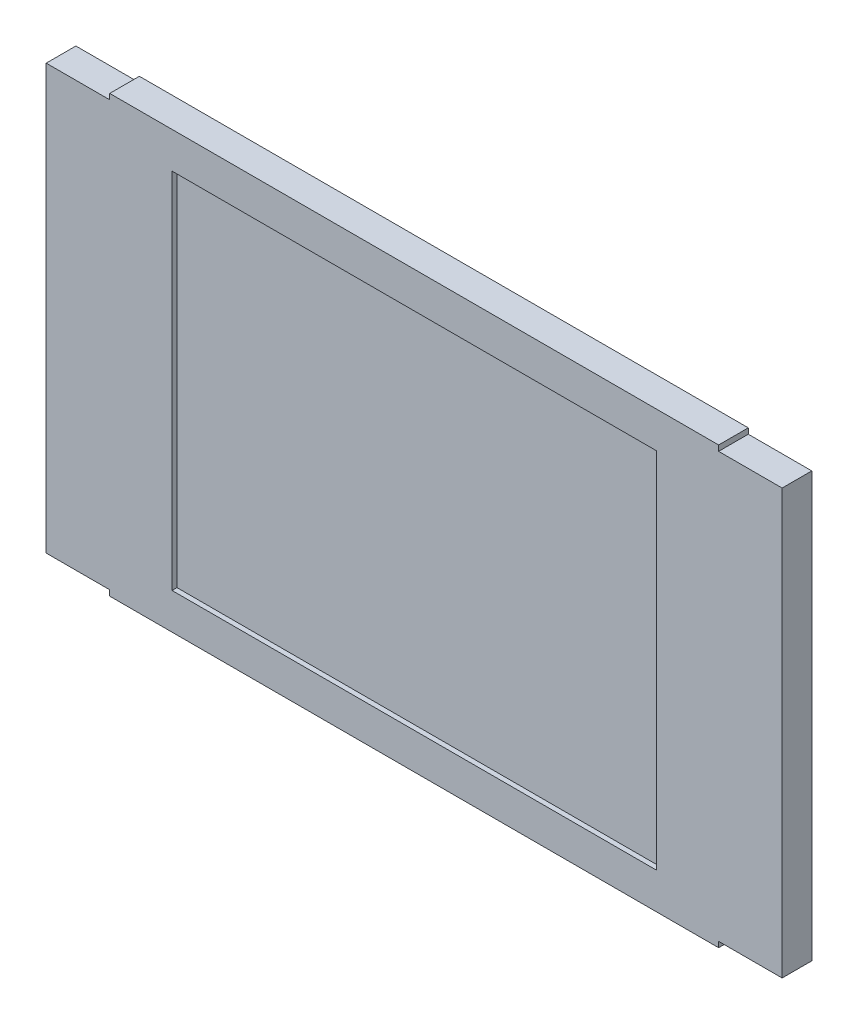
SolidWorks part; units mm, degrees
ref_plane "前视基准面" through (0, 0, 0) normal (0, 0, 1) x (1, 0, 0)
ref_plane "上视基准面" through (0, 0, 0) normal (0, 1, 0) x (1, 0, 0)
ref_plane "右视基准面" through (0, 0, 0) normal (1, 0, 0) x (0, 0, -1)
sketch "草图1" plane through (0, 0, 0) normal (0, 0, 1) x (1, 0, 0)
  line L1 (-37.2, 21.45) -> (37.2, 21.45)
  line L2 (-37.2, 21.45) -> (-37.2, -21.45)
  line L3 (-37.2, -21.45) -> (37.2, -21.45)
  line L4 (37.2, 21.45) -> (37.2, -21.45)
  line L5 (-37.2, 21.45) -> (37.2, -21.45) construction
  line L6 (-37.2, -21.45) -> (37.2, 21.45) construction
  point P0 (0, 0)
  dimension "D1" = 42.9
  dimension "D2" = 74.4
extrude "凸台-拉伸1" add sketch "草图1" along normal blind 3
sketch "草图2" plane through (0, 0, 3) normal (0, 0, 1) x (1, 0, 0)
  line L1 (-30.78, 22.01) -> (30.78, 22.01)
  line L2 (-30.78, 22.01) -> (-30.78, -22.01)
  line L3 (-30.78, -22.01) -> (30.78, -22.01)
  line L4 (30.78, 22.01) -> (30.78, -22.01)
  line L5 (-30.78, 22.01) -> (30.78, -22.01) construction
  line L6 (-30.78, -22.01) -> (30.78, 22.01) construction
  point P0 (0, 0)
  dimension "D1" = 44.02
  dimension "D2" = 61.56
extrude "凸台-拉伸2" add sketch "草图2" against normal blind 3
sketch "草图3" plane through (0, 0, 3) normal (0, 0, 1) x (1, 0, 0)
  line L1 (-24.48, 18.36) -> (24.48, 18.36)
  line L2 (-24.48, 18.36) -> (-24.48, -18.36)
  line L3 (-24.48, -18.36) -> (24.48, -18.36)
  line L4 (24.48, 18.36) -> (24.48, -18.36)
  line L5 (-24.48, 18.36) -> (24.48, -18.36) construction
  line L6 (-24.48, -18.36) -> (24.48, 18.36) construction
  point P0 (0, 0)
  dimension "D1" = 36.72
  dimension "D2" = 48.96
extrude "切除-拉伸2" cut sketch "草图3" against normal blind 0.5
